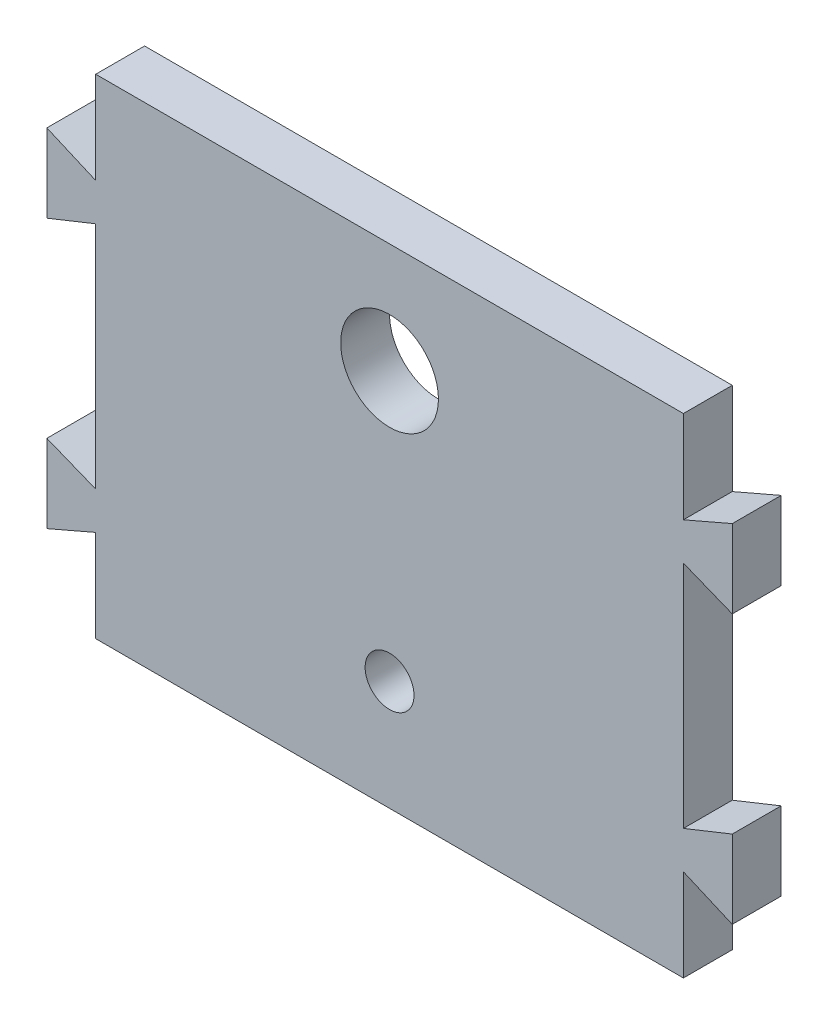
SolidWorks part; units mm, degrees
ref_plane "Front Plane" through (0, 0, 0) normal (0, 0, 1) x (1, 0, 0)
ref_plane "Top Plane" through (0, 0, 0) normal (0, 1, 0) x (1, 0, 0)
ref_plane "Right Plane" through (0, 0, 0) normal (1, 0, 0) x (0, 0, -1)
sketch "Sketch1" plane through (0, 0, 0) normal (0, 0, 1) x (1, 0, 0)
  line L0 (0, 15.8758) -> (38.1703, 15.8758) construction
  line L1 (0, 0) -> (38.1703, 0)
  line L3 (0, 31.7517) -> (38.1703, 31.7517)
  line L5 (19.0852, 31.7517) -> (19.0852, 0) construction
  line L7 (19.0852, 24.6071) -> (0, 24.6071) construction
  line L9 (19.0852, 7.1446) -> (0, 7.1446) construction
  line L17 (-3.175, 24.6071) -> (-3.175, 27.1471)
  line L19 (-3.175, 24.6071) -> (-3.175, 22.0671)
  line L20 (-3.175, 23.3371) -> (0, 23.3371) construction
  line L21 (-3.175, 25.7741) -> (0, 25.7741) construction
  line L25 (-3.175, 7.1446) -> (-3.175, 9.6846)
  line L29 (-3.175, 7.1446) -> (-3.175, 4.6046)
  line L30 (41.3453, 7.1446) -> (41.3453, 4.6046)
  line L34 (41.3453, 7.1446) -> (41.3453, 9.6846)
  line L35 (41.3453, 24.6071) -> (41.3453, 22.0671)
  line L39 (41.3453, 24.6071) -> (41.3453, 27.1471)
  line L47 (0, 31.7517) -> (0, 0)
  line L48 (38.1703, 31.7517) -> (38.1703, 0)
  line L49 (-3.175, 27.1471) -> (0, 25.7741)
  line L50 (-3.175, 22.0671) -> (0, 23.3371)
  line L51 (-3.175, 9.6846) -> (0, 8.4146)
  line L52 (-3.175, 4.6046) -> (0, 5.9775)
  line L53 (0, 25.7741) -> (38.1703, 25.7741) construction
  line L54 (0, 23.3371) -> (38.1703, 23.3371) construction
  line L55 (0, 8.4146) -> (38.1703, 8.4146) construction
  line L56 (0, 5.9775) -> (38.1703, 5.9775) construction
  line L57 (41.3453, 4.6046) -> (38.1703, 5.9775)
  line L58 (41.3453, 9.6846) -> (38.1703, 8.4146)
  line L59 (41.3453, 27.1471) -> (38.1703, 25.7741)
  line L60 (41.3453, 22.0671) -> (38.1703, 23.3371)
  line L61 (0, 25.7741) -> (0, 23.3371)
  line L62 (0, 8.4146) -> (0, 5.9775)
  line L63 (38.1703, 5.9775) -> (38.1703, 8.4146)
  line L64 (38.1703, 25.7741) -> (38.1703, 23.3371)
extrude "Boss-Extrude1" add sketch "Sketch1" along normal blind 3.175 contours L48 L1 L47 L3 | L61 L50 L19 L17 L49 | L62 L52 L29 L25 L51 | L63 L58 L34 L30 L57 | L64 L60 L35 L39 L59
sketch "Sketch2" plane through (0, 0, 3.175) normal (0, 0, 1) x (1, 0, 0)
  line L0 (0, 15.8758) -> (38.1703, 15.8758) construction
  line L1 (0, 23.3371) -> (0, 8.4146) construction
  line L2 (38.1703, 23.3371) -> (38.1703, 8.4146) construction
  circle A0 centre (19.0852, 24.6071) radius 3.175
  circle A1 centre (19.0852, 7.1446) radius 1.5875
  dimension "D1" = 6.35
  dimension "D2" = 3.175
extrude "Cut-Extrude1" cut sketch "Sketch2" against normal blind 3.175
